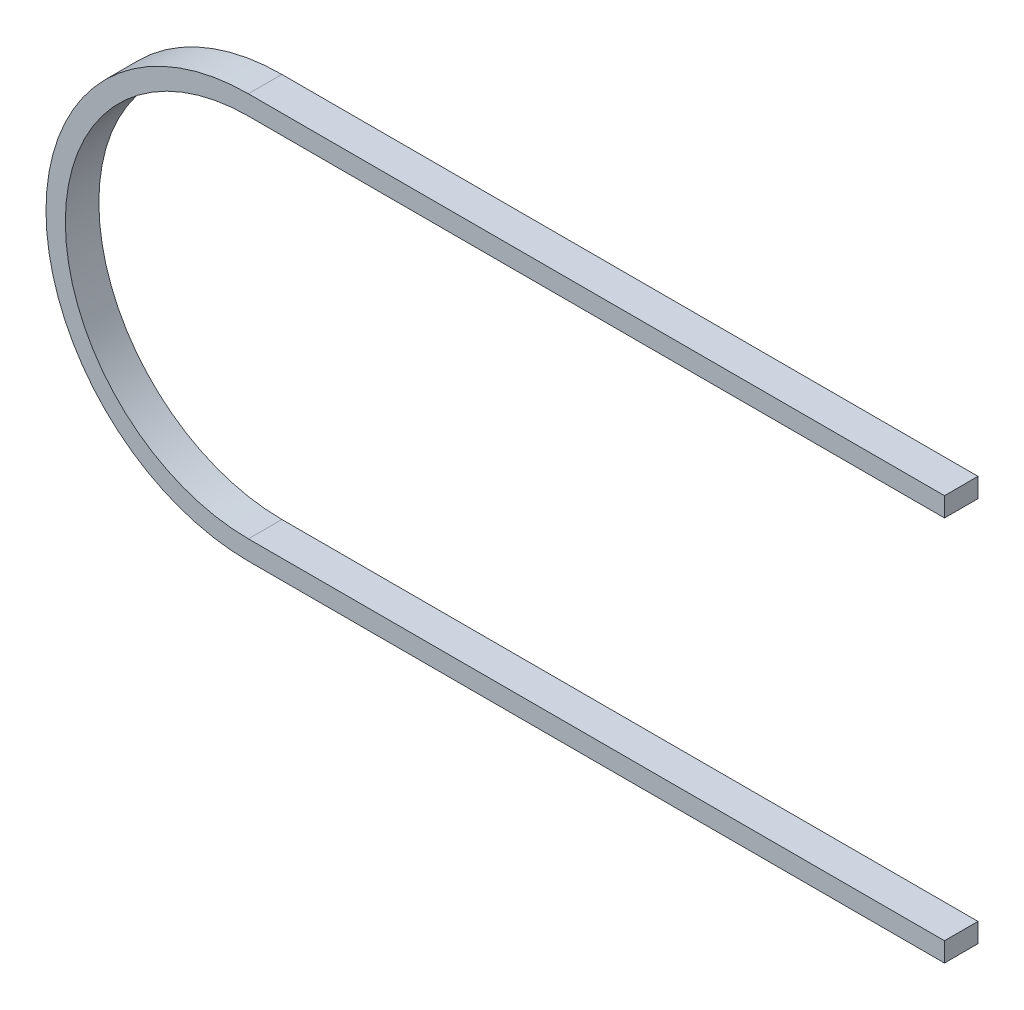
SolidWorks part; units mm, degrees
ref_plane "Front Plane" through (0, 0, 0) normal (0, 0, 1) x (1, 0, 0)
ref_plane "Top Plane" through (0, 0, 0) normal (0, 1, 0) x (1, 0, 0)
ref_plane "Right Plane" through (0, 0, 0) normal (1, 0, 0) x (0, 0, -1)
sketch "Sketch1" plane through (0, 0, 0) normal (0, 0, 1) x (1, 0, 0)
  line L0 (0, 19.939) -> (68.58, 19.939)
  line L1 (0, 18.034) -> (68.58, 18.034)
  line L2 (68.58, 18.034) -> (68.58, 19.939)
  line L3 (0, -18.034) -> (68.58, -18.034)
  line L4 (68.58, -18.034) -> (68.58, -19.939)
  line L5 (68.58, -19.939) -> (0, -19.939)
  arc A0 (0, 19.939) -> (0, -19.939) centre (0, 0) ccw
  arc A1 (0, 18.034) -> (0, -18.034) centre (0, 0) ccw
  dimension "D1" = 68.58
  dimension "D2" = 1.905
  dimension "D3" = 36.068
extrude "Boss-Extrude1" add sketch "Sketch1" along normal blind 3.302
equation "\"wall_thickness\"= 0.125in"
equation "\"base_thickness\"= 0.25in"
